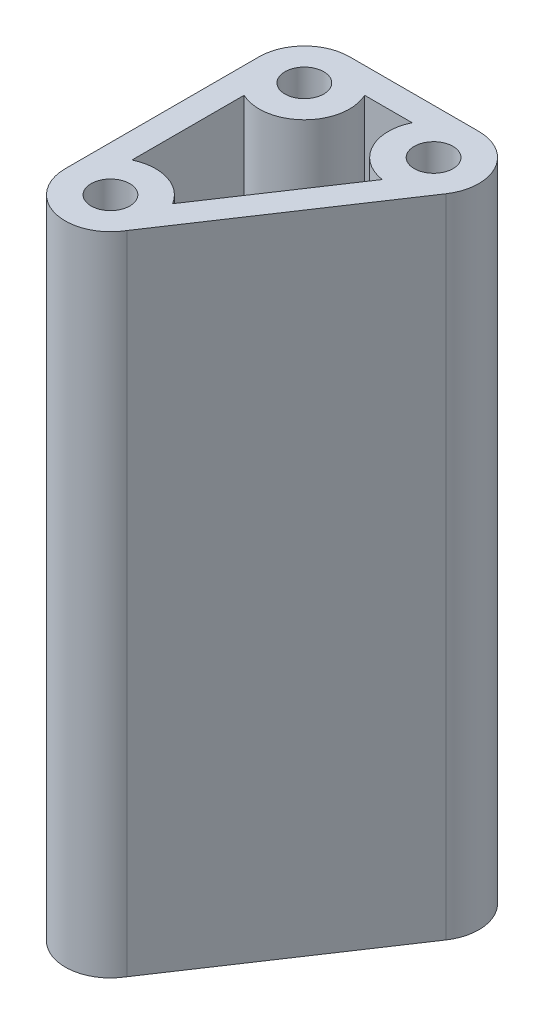
SolidWorks part; units mm, degrees
material "ABS"
ref_plane "Front Plane" through (0, 0, 0) normal (0, 0, 1) x (1, 0, 0)
ref_plane "Top Plane" through (0, 0, 0) normal (0, 1, 0) x (1, 0, 0)
ref_plane "Right Plane" through (0, 0, 0) normal (1, 0, 0) x (0, 0, -1)
sketch "Sketch1" plane through (0, 0, 0) normal (0, 1, 0) x (1, 0, 0)
  line L0 (-11.236, 16.5521) -> (-11.236, 1.5521)
  line L2 (-7.736, 20.0521) -> (2.264, 20.0521)
  line L6 (-4.7049, -0.1979) -> (5.1691, 14.6001)
  line L7 (2.264, 16.5521) -> (5.1691, 14.6001) construction
  line L8 (-7.736, 1.5521) -> (-4.7049, -0.1979) construction
  circle A0 centre (-7.736, 16.5521) radius 1.5
  circle A1 centre (2.264, 16.5521) radius 1.5
  circle A2 centre (-7.736, 1.5521) radius 1.5
  arc A3 (-7.736, 20.0521) -> (-11.236, 16.5521) centre (-7.736, 16.5521) ccw
  arc A4 (5.1691, 14.6001) -> (2.264, 20.0521) centre (2.264, 16.5521) ccw
  arc A5 (-11.236, 1.5521) -> (-4.7049, -0.1979) centre (-7.736, 1.5521) ccw
  circle A6 centre (-7.736, 1.5521) radius 3.5 construction
  circle A7 centre (2.264, 16.5521) radius 3.5 construction
  circle A8 centre (-7.736, 16.5521) radius 3.5 construction
  dimension "D3" = 3
  dimension "D1" = 15
  dimension "D2" = 10
  dimension "D4" = 2
  dimension "D5" = 60
extrude "Boss-Extrude1" add sketch "Sketch1" along normal blind 50
shell "Shell2" thickness 2
sketch "Sketch2" plane through (0, 2, 0) normal (0, 1, 0) x (1, 0, 0)
  line L0 (-9.236, 13.3899) -> (-9.236, 4.7144)
  line L1 (-4.5738, 18.0521) -> (-0.8983, 18.0521)
  line L2 (-4.7373, 3.357) -> (1.7565, 13.0891)
  arc A0 (-9.236, 4.7144) -> (-4.7373, 3.357) centre (-7.736, 1.5521) cw
  arc A1 (-0.8983, 18.0521) -> (1.7565, 13.0891) centre (2.264, 16.5521) ccw
  arc A2 (-4.5738, 18.0521) -> (-9.236, 13.3899) centre (-7.736, 16.5521) cw
extrude "Cut-Extrude1" cut sketch "Sketch2" against normal through all
